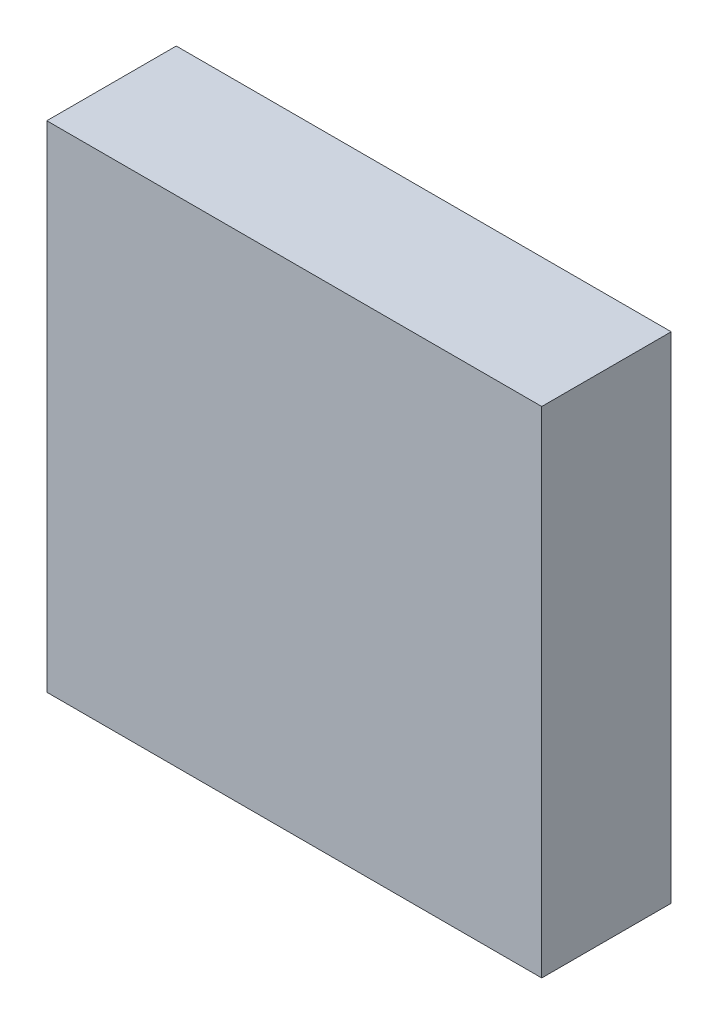
SolidWorks part; units mm, degrees
ref_plane "前视基准面" through (0, 0, 0) normal (0, 0, 1) x (1, 0, 0)
ref_plane "上视基准面" through (0, 0, 0) normal (0, 1, 0) x (1, 0, 0)
ref_plane "右视基准面" through (0, 0, 0) normal (1, 0, 0) x (0, 0, -1)
sketch "草图1" plane through (0, 0, 0) normal (0, 0, 1) x (1, 0, 0)
  line L0 (-3.25, -3.25) -> (-3.25, 3.25)
  line L1 (-3.25, 3.25) -> (3.25, 3.25)
  line L2 (3.25, 3.25) -> (3.25, -3.25)
  line L3 (3.25, -3.25) -> (-3.25, -3.25)
extrude "Component_Outline" add sketch "草图1" along normal blind 1.7 separate body
sketch3d "3D草图1"
  line L0 (0, 0, 0) -> (1, 0, 0)
  line L1 (0, 0, 0) -> (0, 1, 0)
  line L2 (0, 0, 0) -> (0, 0, 1)
  point P0 (0, 0, 0)
